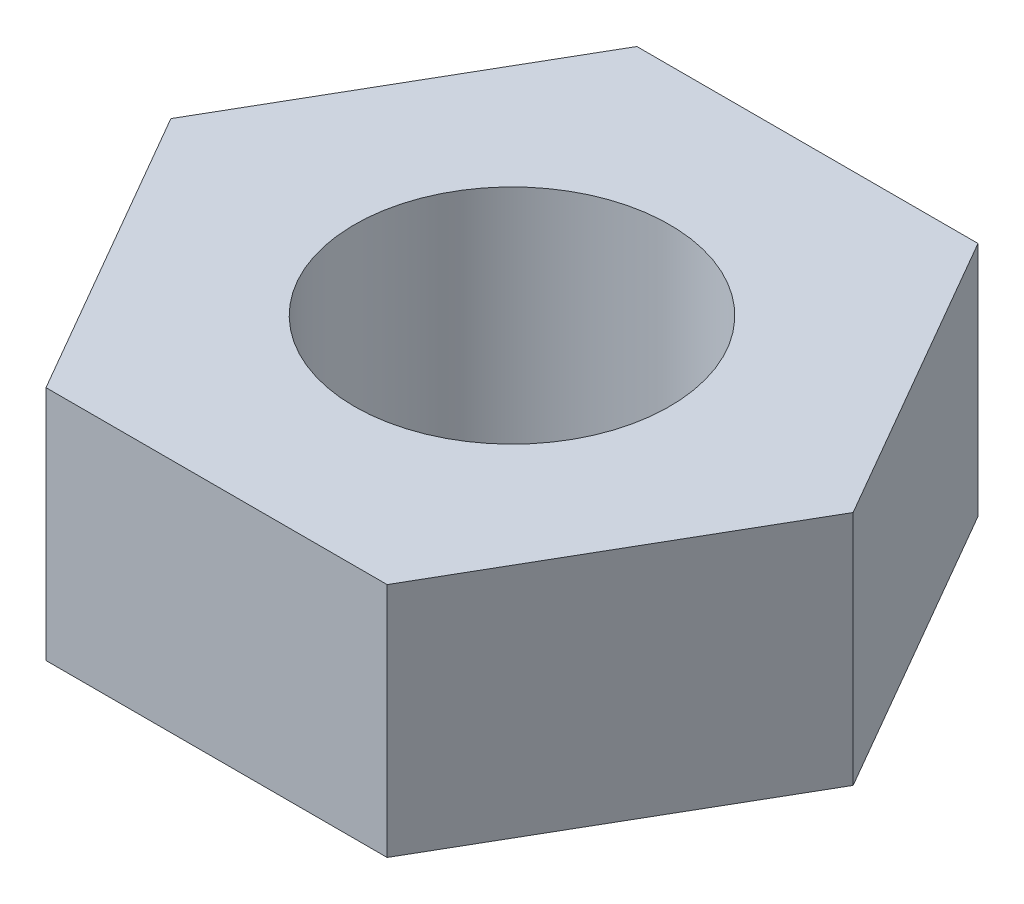
SolidWorks part; units mm, degrees
material "Alloy Steel"
ref_plane "Front Plane" through (0, 0, 0) normal (0, 0, 1) x (1, 0, 0)
ref_plane "Top Plane" through (0, 0, 0) normal (0, 1, 0) x (1, 0, 0)
ref_plane "Right Plane" through (0, 0, 0) normal (1, 0, 0) x (0, 0, -1)
sketch "Sketch1" plane through (0, 0, 0) normal (0, 1, 0) x (1, 0, 0)
  line L1 (4.3301, 0) -> (2.1651, 3.75)
  line L2 (2.1651, 3.75) -> (-2.1651, 3.75)
  line L3 (-2.1651, 3.75) -> (-4.3301, 0)
  line L4 (-4.3301, 0) -> (-2.1651, -3.75)
  line L5 (-2.1651, -3.75) -> (2.1651, -3.75)
  line L6 (2.1651, -3.75) -> (4.3301, 0)
  circle A0 centre (0, 0) radius 3.75 construction
  circle A1 centre (0, 0) radius 2
  dimension "D1" = 7.5
  dimension "D2" = 4
extrude "Boss-Extrude1" add sketch "Sketch1" along normal blind 3
